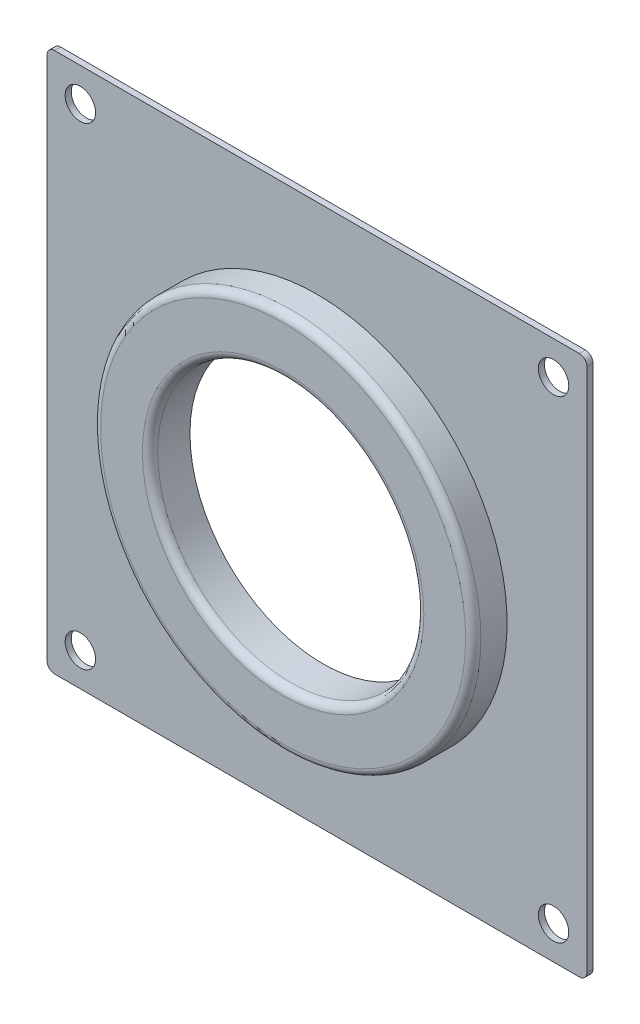
SolidWorks part; units mm, degrees
ref_plane "前视基准面" through (0, 0, 0) normal (0, 0, 1) x (1, 0, 0)
ref_plane "上视基准面" through (0, 0, 0) normal (0, 1, 0) x (1, 0, 0)
ref_plane "右视基准面" through (0, 0, 0) normal (1, 0, 0) x (0, 0, -1)
ref_plane "基准面1" through (0, 0, 1) normal (0, 0, 1) x (1, 0, 0)
sketch "草图1" plane through (0, 0, 1) normal (0, 0, 1) x (1, 0, 0)
  line L0 (-35.5, 35.5) -> (-35.5, -35.5)
  line L1 (-35.5, -35.5) -> (35.5, -35.5)
  line L2 (35.5, -35.5) -> (35.5, 35.5)
  line L3 (35.5, 35.5) -> (-35.5, 35.5)
extrude "凸台-拉伸1" add sketch "草图1" against normal blind 0.8
ref_plane "基准面2" through (0, 0, 0) normal (0, -1, 0) x (1, 0, 0)
sketch "草图2" plane through (0, 0, 0) normal (0, -1, 0) x (1, 0, 0)
  line L0 (25, 5.45) -> (0, 5.45)
  line L1 (0, 5.45) -> (0, 1)
  line L2 (0, 1) -> (25, 1)
  line L3 (25, 1) -> (25, 5.45)
  line L4 (0, 5.45) -> (0, 1) construction
  dimension "D1" = 4.45
revolve "旋转1" add sketch "草图2" angle 360 about L4
hole_wizard "M30 间隙孔1" positions "草图4" profile "草图3" hole size "M30" standard "ANSI Metric"
sketch "草图4" plane through (0, 0, 5.45) normal (0, 0, 1) x (1, 0, 0)
  point P0 (0, 0)
sketch "草图3" plane through (0, 0, 5.45) normal (1, 0, 0) x (0, -1, 0)
  line L0 (0, 0) -> (0, 5.25)
  line L1 (0, 5.25) -> (17.5, 5.25)
  line L2 (17.5, 5.25) -> (17.5, 0)
  line L5 (17.5, 0) -> (0, 0)
  line L11 (0, -6.35) -> (0, 107.95) construction
  dimension "通孔孔直径" = 35
  dimension "通孔孔深度" = 5.25
hole_wizard "Ø4.0 (4) 直径孔1" positions "草图6" profile "草图5" hole size "Ø4.0" standard "ANSI Metric"
sketch "草图6" plane through (0, 0, 1) normal (0, 0, 1) x (1, 0, 0)
  point P0 (-29, 29)
  point P1 (-29, -29)
  point P2 (29, -29)
  point P3 (29, 29)
sketch "草图5" plane through (-29, 29, 1) normal (1, 0, 0) x (0, -1, 0)
  line L0 (0, 0) -> (0, 0.8)
  line L1 (0, 0.8) -> (2, 0.8)
  line L2 (2, 0.8) -> (2, 0)
  line L5 (2, 0) -> (0, 0)
  line L11 (0, -6.35) -> (0, 107.95) construction
  dimension "通孔孔直径" = 4
  dimension "通孔孔深度" = 0.8
fillet "圆角1" radius 1 2 edges at (17.5, 0, 5.45) (-25, 0, 5.45)
fillet "圆角2" radius 10 4 edges at (35.5, -35.5, 0.6) (-35.5, -35.5, 0.6) (-35.5, 35.5, 0.6) (35.5, 35.5, 0.6)
sketch "草图8" plane through (0, 0, 1) normal (0, 0, 1) x (1, 0, 0)
  circle A5 centre (-31.1127, 31.1127) radius 2
  circle A6 centre (31.1127, -31.1127) radius 2
  circle A8 centre (0, 0) radius 17.5 construction
  circle A9 centre (-31.1127, -31.1127) radius 2
  circle A10 centre (31.1127, 31.1127) radius 2
  dimension "D1" = 44
  dimension "D2" = 44
  dimension "D3" = 4
  dimension "D4" = 4
  dimension "D5" = 4
  dimension "D6" = 44
  dimension "D7" = 4
  dimension "D8" = 44
sketch "草图9" plane through (0, 0, 1) normal (0, 0, 1) x (1, 0, 0)
  line L0 (-34.5, 35.5) -> (34.5, 35.5)
  line L1 (34.5, -35.5) -> (-34.5, -35.5)
  line L5 (-35.5, 34.5) -> (-35.5, -34.5)
  line L9 (35.5, 34.5) -> (35.5, -34.5)
  circle A0 centre (0, 0) radius 17.5
  arc A2 (-34.5, 35.5) -> (-35.5, 34.5) centre (-34.5, 34.5) ccw
  arc A3 (-34.5, -35.5) -> (-35.5, -34.5) centre (-34.5, -34.5) cw
  arc A4 (35.5, -34.5) -> (34.5, -35.5) centre (34.5, -34.5) cw
  arc A5 (35.5, 34.5) -> (34.5, 35.5) centre (34.5, 34.5) ccw
  dimension "D1" = 1
  dimension "D2" = 1
extrude "凸台-拉伸3" add sketch "草图9" against normal blind 0.8
extrude "切除-拉伸1" cut sketch "草图8" against normal up to next
